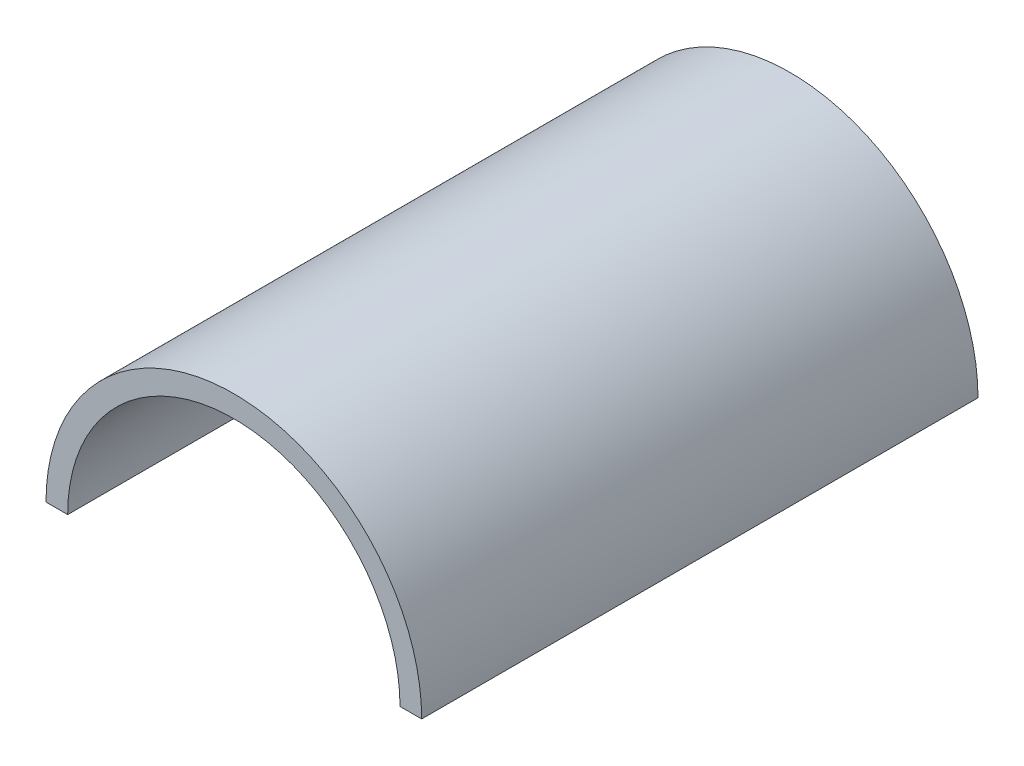
SolidWorks part; units mm, degrees
ref_plane "Front Plane" through (0, 0, 0) normal (0, 0, 1) x (1, 0, 0)
ref_plane "Top Plane" through (0, 0, 0) normal (0, 1, 0) x (1, 0, 0)
ref_plane "Right Plane" through (0, 0, 0) normal (1, 0, 0) x (0, 0, -1)
sketch "Sketch1" plane through (0, 0, 0) normal (0, 0, 1) x (1, 0, 0)
  line L0 (-23, 0) -> (23, 0) construction
  line L1 (-23, 0) -> (-26, 0)
  line L2 (23, 0) -> (26, 0)
  arc A0 (26, 0) -> (-26, 0) centre (0, 0) ccw
  arc A1 (23, 0) -> (-23, 0) centre (0, 0) ccw
  point P7 (0, 0)
  dimension "D1" = 3
  dimension "D2" = 52
extrude "Boss-Extrude1" add sketch "Sketch1" along normal blind 77
